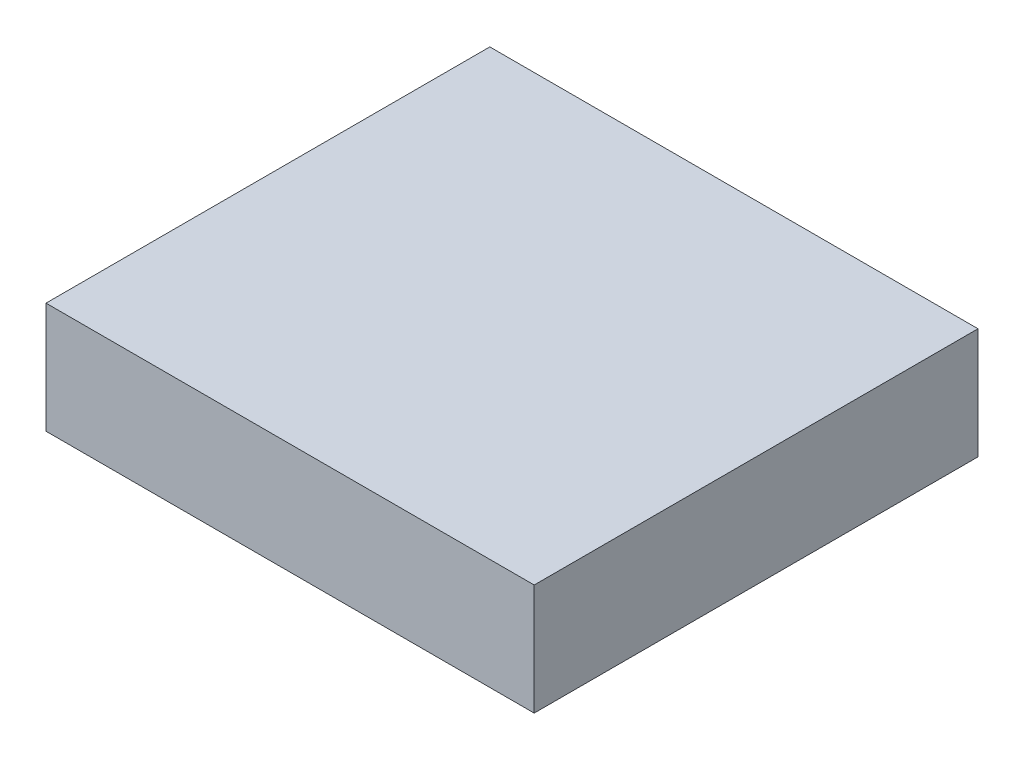
SolidWorks part; units mm, degrees
ref_plane "Front Plane" through (0, 0, 0) normal (0, 0, 1) x (1, 0, 0)
ref_plane "Top Plane" through (0, 0, 0) normal (0, 1, 0) x (1, 0, 0)
ref_plane "Right Plane" through (0, 0, 0) normal (1, 0, 0) x (0, 0, -1)
sketch "Sketch1" plane through (0, 0, 0) normal (0, 1, 0) x (1, 0, 0)
  line L1 (-55, 50) -> (55, 50)
  line L2 (-55, 50) -> (-55, -50)
  line L3 (-55, -50) -> (55, -50)
  line L4 (55, 50) -> (55, -50)
  line L5 (-55, 50) -> (55, -50) construction
  line L6 (-55, -50) -> (55, 50) construction
  point P0 (0, 0)
  dimension "D1" = 100
  dimension "D2" = 110
extrude "Boss-Extrude1" add sketch "Sketch1" along normal blind 25
